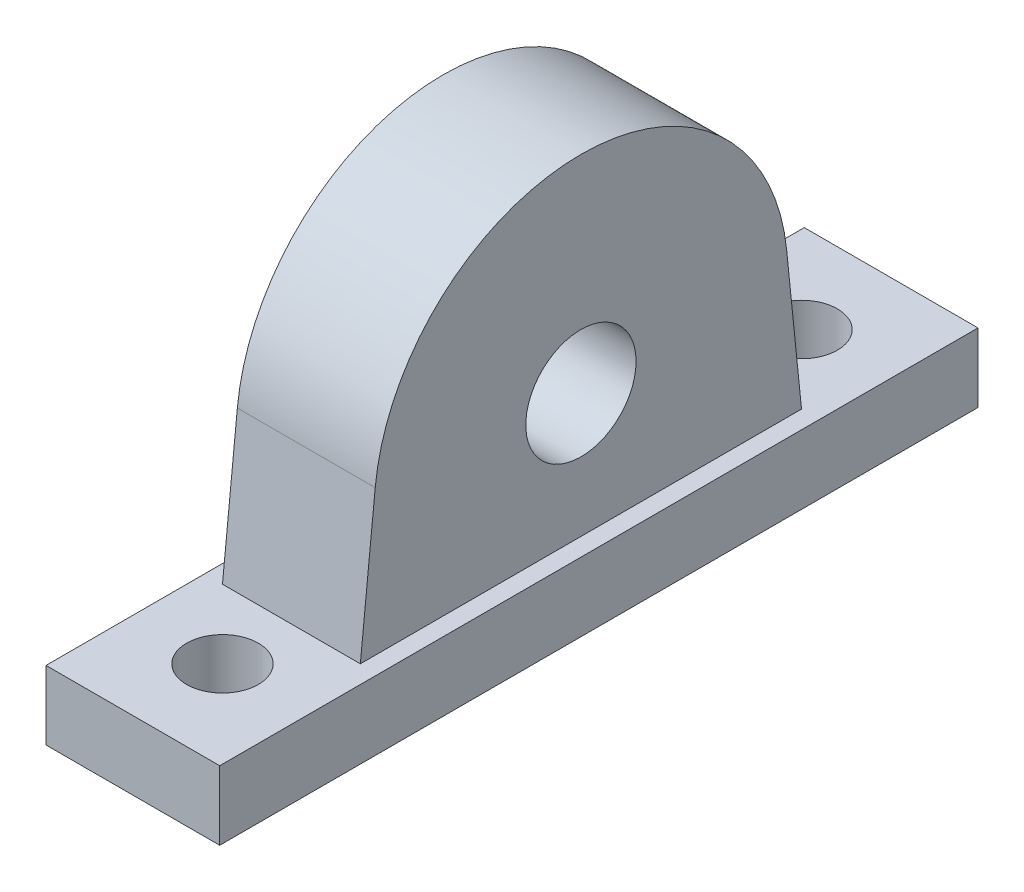
SolidWorks part; units mm, degrees
material "6061 合金"
ref_plane "前视基准面" through (0, 0, 0) normal (0, 0, 1) x (1, 0, 0)
ref_plane "上视基准面" through (0, 0, 0) normal (0, 1, 0) x (1, 0, 0)
ref_plane "右视基准面" through (0, 0, 0) normal (1, 0, 0) x (0, 0, -1)
other "Configuration Table"
sketch "草图1" plane through (0, 0, 0) normal (0, 1, 0) x (1, 0, 0)
  line L0 (0, 27.5) -> (0, -27.5) construction
  line L1 (-6.3, -27.5) -> (6.3, -27.5)
  line L2 (-6.3, -27.5) -> (-6.3, 27.5)
  line L3 (-6.3, 27.5) -> (6.3, 27.5)
  line L4 (6.3, -27.5) -> (6.3, 27.5)
  line L5 (-6.3, -27.5) -> (6.3, 27.5) construction
  line L6 (-6.3, 27.5) -> (6.3, -27.5) construction
  circle A0 centre (0, 21) radius 2.6
  circle A1 centre (0, -21) radius 2.6
  point P0 (0, 0)
  dimension "D3" = 5.2
  dimension "D4" = 21
  dimension "D5" = 42
  dimension "D1" = 12.6
  dimension "D2" = 55
extrude "凸台-拉伸1" add sketch "草图1" along normal blind 5
sketch "草图2" plane through (0, 0, 0) normal (1, 0, 0) x (0, 0, -1)
  line L0 (-16, 5) -> (-14.922, 15.528)
  line L1 (-27.5, 5) -> (27.5, 5) construction
  line L2 (14.922, 15.528) -> (16, 5)
  line L3 (0, 0) -> (0, 14) construction
  line L4 (-16, 5) -> (16, 5)
  arc A0 (-14.922, 15.528) -> (14.922, 15.528) centre (0, 14) cw
  circle A1 centre (0, 14) radius 4
  point P10 (16.4908, 5)
  dimension "D1" = 15
  dimension "D3" = 8
  dimension "D2" = 14
  dimension "D4" = 32
extrude "凸台-拉伸2" add sketch "草图2" along normal mid plane 10
